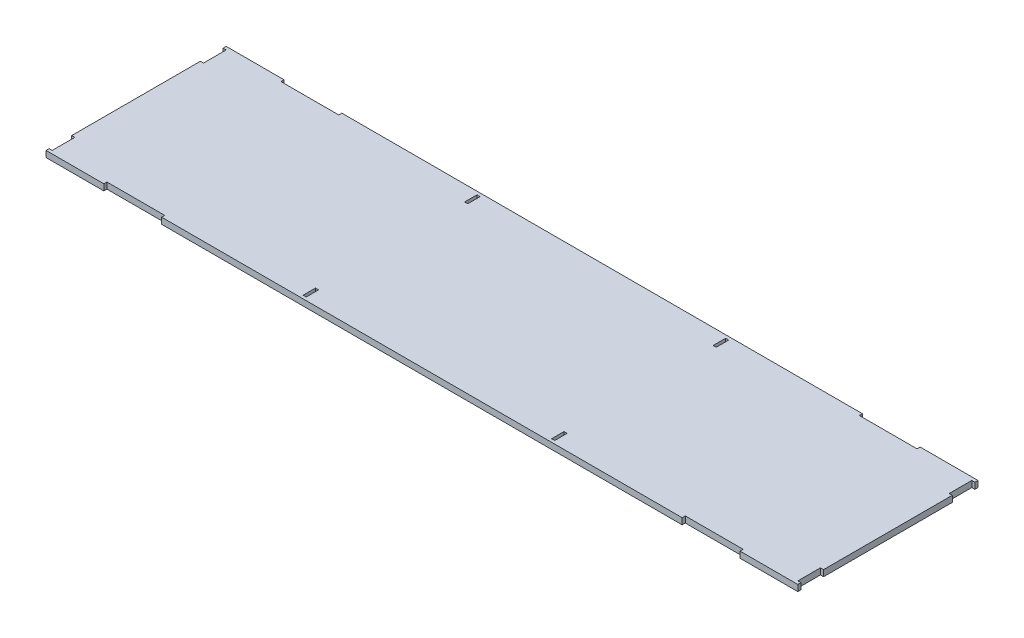
SolidWorks part; units mm, degrees
ref_plane "Front Plane" through (0, 0, 0) normal (0, 0, 1) x (1, 0, 0)
ref_plane "Top Plane" through (0, 0, 0) normal (0, 1, 0) x (1, 0, 0)
ref_plane "Right Plane" through (0, 0, 0) normal (1, 0, 0) x (0, 0, -1)
sketch "Sketch1" plane through (0, 0, 0) normal (0, 1, 0) x (1, 0, 0)
  line L0 (0, 88.9) -> (0, -88.9) construction
  line L1 (-381, 88.9) -> (381, 88.9)
  line L2 (-381, 88.9) -> (-381, -88.9)
  line L3 (-381, -88.9) -> (381, -88.9)
  line L4 (381, 88.9) -> (381, -88.9)
  line L5 (-381, 39.4607) -> (-381, 65.7679)
  line L6 (-381, 65.7679) -> (-384.175, 65.7679)
  line L7 (-381, 65.7679) -> (-381, 92.075)
  line L8 (-381, 92.075) -> (-384.175, 92.075)
  line L9 (-384.175, 65.7679) -> (-384.175, 92.075)
  line L14 (-325.0712, -88.9) -> (-384.175, -88.9)
  line L15 (-325.0712, -88.9) -> (-325.0712, -92.075)
  line L16 (-325.0712, -92.075) -> (-384.175, -92.075)
  line L17 (-384.175, -88.9) -> (-384.175, -92.075)
  line L18 (381, 65.7679) -> (384.175, 65.7679)
  line L19 (381, 65.7679) -> (381, 92.075)
  line L20 (381, 92.075) -> (384.175, 92.075)
  line L21 (384.175, 65.7679) -> (384.175, 92.075)
  line L22 (-325.0712, 88.9) -> (-384.175, 88.9)
  line L23 (-325.0712, 88.9) -> (-325.0712, 92.075)
  line L24 (-325.0712, 92.075) -> (-384.175, 92.075)
  line L25 (-384.175, 88.9) -> (-384.175, 92.075)
  line L26 (-381, 39.4607) -> (-384.175, 39.4607)
  line L27 (-384.175, 39.4607) -> (-384.175, 65.7679)
  line L28 (-381, 65.7679) -> (-384.175, 65.7679)
  line L29 (381, 39.4607) -> (381, 65.7679)
  line L30 (381, 39.4607) -> (384.175, 39.4607)
  line L31 (384.175, 39.4607) -> (384.175, 65.7679)
  line L32 (381, 65.7679) -> (384.175, 65.7679)
  line L33 (-381, 13.1536) -> (-381, 39.4607)
  line L34 (-381, 13.1536) -> (-384.175, 13.1536)
  line L35 (-384.175, 13.1536) -> (-384.175, 39.4607)
  line L36 (-381, 39.4607) -> (-384.175, 39.4607)
  line L37 (381, 13.1536) -> (381, 39.4607)
  line L38 (381, 13.1536) -> (384.175, 13.1536)
  line L39 (384.175, 13.1536) -> (384.175, 39.4607)
  line L40 (381, 39.4607) -> (384.175, 39.4607)
  line L41 (-381, -13.1536) -> (-381, 13.1536)
  line L42 (-381, -13.1536) -> (-384.175, -13.1536)
  line L43 (-384.175, -13.1536) -> (-384.175, 13.1536)
  line L44 (-381, 13.1536) -> (-384.175, 13.1536)
  line L45 (381, -13.1536) -> (381, 13.1536)
  line L46 (381, -13.1536) -> (384.175, -13.1536)
  line L47 (384.175, -13.1536) -> (384.175, 13.1536)
  line L48 (381, 13.1536) -> (384.175, 13.1536)
  line L49 (-381, -39.4607) -> (-381, -13.1536)
  line L50 (-381, -39.4607) -> (-384.175, -39.4607)
  line L51 (-384.175, -39.4607) -> (-384.175, -13.1536)
  line L52 (-381, -13.1536) -> (-384.175, -13.1536)
  line L53 (381, -39.4607) -> (381, -13.1536)
  line L54 (381, -39.4607) -> (384.175, -39.4607)
  line L55 (384.175, -39.4607) -> (384.175, -13.1536)
  line L56 (381, -13.1536) -> (384.175, -13.1536)
  line L57 (-381, -65.7679) -> (-381, -39.4607)
  line L58 (-381, -65.7679) -> (-384.175, -65.7679)
  line L59 (-384.175, -65.7679) -> (-384.175, -39.4607)
  line L60 (-381, -39.4607) -> (-384.175, -39.4607)
  line L61 (381, -65.7679) -> (381, -39.4607)
  line L62 (381, -65.7679) -> (384.175, -65.7679)
  line L63 (384.175, -65.7679) -> (384.175, -39.4607)
  line L64 (381, -39.4607) -> (384.175, -39.4607)
  line L65 (-381, -92.075) -> (-381, -65.7679)
  line L66 (-381, -92.075) -> (-384.175, -92.075)
  line L67 (-384.175, -92.075) -> (-384.175, -65.7679)
  line L68 (-381, -65.7679) -> (-384.175, -65.7679)
  line L69 (381, -92.075) -> (381, -65.7679)
  line L70 (381, -92.075) -> (384.175, -92.075)
  line L71 (384.175, -92.075) -> (384.175, -65.7679)
  line L72 (381, -65.7679) -> (384.175, -65.7679)
  line L73 (-265.9673, -88.9) -> (-265.9673, -92.075)
  line L74 (-265.9673, -88.9) -> (-325.0712, -88.9)
  line L75 (-325.0712, -88.9) -> (-325.0712, -92.075)
  line L76 (-265.9673, -92.075) -> (-325.0712, -92.075)
  line L77 (-265.9673, 88.9) -> (-265.9673, 92.075)
  line L78 (-265.9673, 88.9) -> (-325.0712, 88.9)
  line L79 (-325.0712, 88.9) -> (-325.0712, 92.075)
  line L80 (-265.9673, 92.075) -> (-325.0712, 92.075)
  line L81 (-206.8635, -88.9) -> (-206.8635, -92.075)
  line L82 (-206.8635, -88.9) -> (-265.9673, -88.9)
  line L83 (-265.9673, -88.9) -> (-265.9673, -92.075)
  line L84 (-206.8635, -92.075) -> (-265.9673, -92.075)
  line L85 (-206.8635, 88.9) -> (-206.8635, 92.075)
  line L86 (-206.8635, 88.9) -> (-265.9673, 88.9)
  line L87 (-265.9673, 88.9) -> (-265.9673, 92.075)
  line L88 (-206.8635, 92.075) -> (-265.9673, 92.075)
  line L89 (-147.7596, -88.9) -> (-147.7596, -92.075)
  line L90 (-147.7596, -88.9) -> (-206.8635, -88.9)
  line L91 (-206.8635, -88.9) -> (-206.8635, -92.075)
  line L92 (-147.7596, -92.075) -> (-206.8635, -92.075)
  line L93 (-147.7596, 88.9) -> (-147.7596, 92.075)
  line L94 (-147.7596, 88.9) -> (-206.8635, 88.9)
  line L95 (-206.8635, 88.9) -> (-206.8635, 92.075)
  line L96 (-147.7596, 92.075) -> (-206.8635, 92.075)
  line L97 (-88.6558, -88.9) -> (-88.6558, -92.075)
  line L98 (-88.6558, -88.9) -> (-147.7596, -88.9)
  line L99 (-147.7596, -88.9) -> (-147.7596, -92.075)
  line L100 (-88.6558, -92.075) -> (-147.7596, -92.075)
  line L101 (-88.6558, 88.9) -> (-88.6558, 92.075)
  line L102 (-88.6558, 88.9) -> (-147.7596, 88.9)
  line L103 (-147.7596, 88.9) -> (-147.7596, 92.075)
  line L104 (-88.6558, 92.075) -> (-147.7596, 92.075)
  line L105 (-29.5519, -88.9) -> (-29.5519, -92.075)
  line L106 (-29.5519, -88.9) -> (-88.6558, -88.9)
  line L107 (-88.6558, -88.9) -> (-88.6558, -92.075)
  line L108 (-29.5519, -92.075) -> (-88.6558, -92.075)
  line L109 (-29.5519, 88.9) -> (-29.5519, 92.075)
  line L110 (-29.5519, 88.9) -> (-88.6558, 88.9)
  line L111 (-88.6558, 88.9) -> (-88.6558, 92.075)
  line L112 (-29.5519, 92.075) -> (-88.6558, 92.075)
  line L113 (29.5519, -88.9) -> (29.5519, -92.075)
  line L114 (29.5519, -88.9) -> (-29.5519, -88.9)
  line L115 (-29.5519, -88.9) -> (-29.5519, -92.075)
  line L116 (29.5519, -92.075) -> (-29.5519, -92.075)
  line L117 (29.5519, 88.9) -> (29.5519, 92.075)
  line L118 (29.5519, 88.9) -> (-29.5519, 88.9)
  line L119 (-29.5519, 88.9) -> (-29.5519, 92.075)
  line L120 (29.5519, 92.075) -> (-29.5519, 92.075)
  line L121 (88.6558, -88.9) -> (88.6558, -92.075)
  line L122 (88.6558, -88.9) -> (29.5519, -88.9)
  line L123 (29.5519, -88.9) -> (29.5519, -92.075)
  line L124 (88.6558, -92.075) -> (29.5519, -92.075)
  line L125 (88.6558, 88.9) -> (88.6558, 92.075)
  line L126 (88.6558, 88.9) -> (29.5519, 88.9)
  line L127 (29.5519, 88.9) -> (29.5519, 92.075)
  line L128 (88.6558, 92.075) -> (29.5519, 92.075)
  line L129 (147.7596, -88.9) -> (147.7596, -92.075)
  line L130 (147.7596, -88.9) -> (88.6558, -88.9)
  line L131 (88.6558, -88.9) -> (88.6558, -92.075)
  line L132 (147.7596, -92.075) -> (88.6558, -92.075)
  line L133 (147.7596, 88.9) -> (147.7596, 92.075)
  line L134 (147.7596, 88.9) -> (88.6558, 88.9)
  line L135 (88.6558, 88.9) -> (88.6558, 92.075)
  line L136 (147.7596, 92.075) -> (88.6558, 92.075)
  line L137 (206.8635, -88.9) -> (206.8635, -92.075)
  line L138 (206.8635, -88.9) -> (147.7596, -88.9)
  line L139 (147.7596, -88.9) -> (147.7596, -92.075)
  line L140 (206.8635, -92.075) -> (147.7596, -92.075)
  line L141 (206.8635, 88.9) -> (206.8635, 92.075)
  line L142 (206.8635, 88.9) -> (147.7596, 88.9)
  line L143 (147.7596, 88.9) -> (147.7596, 92.075)
  line L144 (206.8635, 92.075) -> (147.7596, 92.075)
  line L145 (265.9673, -88.9) -> (265.9673, -92.075)
  line L146 (265.9673, -88.9) -> (206.8635, -88.9)
  line L147 (206.8635, -88.9) -> (206.8635, -92.075)
  line L148 (265.9673, -92.075) -> (206.8635, -92.075)
  line L149 (265.9673, 88.9) -> (265.9673, 92.075)
  line L150 (265.9673, 88.9) -> (206.8635, 88.9)
  line L151 (206.8635, 88.9) -> (206.8635, 92.075)
  line L152 (265.9673, 92.075) -> (206.8635, 92.075)
  line L185 (325.0712, -88.9) -> (325.0712, -92.075)
  line L186 (325.0712, -88.9) -> (265.9673, -88.9)
  line L187 (265.9673, -88.9) -> (265.9673, -92.075)
  line L188 (325.0712, -92.075) -> (265.9673, -92.075)
  line L189 (325.0712, 88.9) -> (325.0712, 92.075)
  line L190 (325.0712, 88.9) -> (265.9673, 88.9)
  line L191 (265.9673, 88.9) -> (265.9673, 92.075)
  line L192 (325.0712, 92.075) -> (265.9673, 92.075)
  line L193 (384.175, -88.9) -> (384.175, -92.075)
  line L194 (384.175, -88.9) -> (325.0712, -88.9)
  line L195 (325.0712, -88.9) -> (325.0712, -92.075)
  line L196 (384.175, -92.075) -> (325.0712, -92.075)
  line L197 (384.175, 88.9) -> (384.175, 92.075)
  line L198 (384.175, 88.9) -> (325.0712, 88.9)
  line L199 (325.0712, 88.9) -> (325.0712, 92.075)
  line L200 (384.175, 92.075) -> (325.0712, 92.075)
  point P8 (0, 88.9)
  point P9 (0, 0)
  dimension "D1" = 762
  dimension "D2" = 177.8
  dimension "D3" = 184.15
  dimension "D5" = 768.35
  dimension "D6" = 26.3071
  dimension "D8" = 59.1038
  dimension "D4" = 7
  dimension "D7" = 13
extrude "Boss-Extrude1" add sketch "Sketch1" along normal blind 6.35
sketch "Sketch2" plane through (0, 6.35, 0) normal (0, 1, 0) x (1, 0, 0)
  line L0 (-125.4125, 0) -> (125.4125, 0) construction
  line L1 (-128.5875, 15.4404) -> (-125.4125, 15.4404) construction
  line L2 (-128.5875, 15.4404) -> (-128.5875, -15.4404) construction
  line L3 (-128.5875, -15.4404) -> (-125.4125, -15.4404) construction
  line L4 (-125.4125, 15.4404) -> (-125.4125, -15.4404) construction
  line L5 (125.4125, 14.3164) -> (128.5875, 14.3164) construction
  line L6 (125.4125, 14.3164) -> (125.4125, -14.3164) construction
  line L7 (125.4125, -14.3164) -> (128.5875, -14.3164) construction
  line L8 (128.5875, 14.3164) -> (128.5875, -14.3164) construction
  line L9 (-129.3813, 24.6215) -> (-124.6188, 24.6215) construction
  line L10 (-127, 24.6215) -> (-127, 15.4404) construction
  line L12 (-124.6188, 76.2) -> (-121.4438, 76.2)
  line L13 (-124.6188, 76.2) -> (-124.6188, 88.9)
  line L14 (-124.6188, 88.9) -> (-121.4438, 88.9)
  line L15 (-121.4438, 76.2) -> (-121.4438, 88.9)
  line L16 (-124.6188, 24.6215) -> (-124.6188, 76.2) construction
  line L18 (-121.4438, -88.9) -> (-124.6188, -88.9)
  line L19 (-121.4438, -88.9) -> (-121.4438, -76.2)
  line L20 (-121.4438, -76.2) -> (-124.6188, -76.2)
  line L21 (-124.6188, -88.9) -> (-124.6188, -76.2)
  line L31 (-206.8635, 88.9) -> (-147.7596, 88.9) construction
  line L32 (-206.8635, -88.9) -> (-147.7596, -88.9) construction
  line L33 (129.3813, 76.2) -> (129.3812, 88.9)
  line L34 (129.3813, 76.2) -> (132.5562, 76.2)
  line L35 (132.5562, 76.2) -> (132.5562, 88.9)
  line L36 (129.3812, 88.9) -> (132.5562, 88.9)
  line L37 (132.5562, -88.9) -> (132.5562, -76.2)
  line L38 (132.5562, -88.9) -> (129.3812, -88.9)
  line L39 (129.3812, -88.9) -> (129.3812, -76.2)
  line L40 (132.5562, -76.2) -> (129.3812, -76.2)
  line L41 (124.6188, 24.6215) -> (129.3813, 24.6215) construction
  line L42 (127, 24.6215) -> (127, 14.3164) construction
  line L43 (129.3813, 24.6215) -> (129.3813, 76.2) construction
  point P10 (0, 0)
  point P43 (127, 14.3164)
  dimension "D1" = 3.175
  dimension "D2" = 4.7625
  dimension "D4" = 3.175
  dimension "D5" = 12.7
  dimension "D3" = 254
  dimension "D6" = 2
extrude "Cut-Extrude1" cut sketch "Sketch2" against normal through all
sketch "Sketch3" plane through (0, 6.35, 0) normal (0, 1, 0) x (1, 0, 0)
  line L1 (-206.8635, -92.075) -> (-147.7596, -92.075)
  line L2 (-206.8635, -92.075) -> (-206.8635, -88.9)
  line L3 (-206.8635, -88.9) -> (-147.7596, -88.9)
  line L4 (-147.7596, -92.075) -> (-147.7596, -88.9)
  line L5 (-88.6558, -92.075) -> (-29.5519, -92.075)
  line L6 (-88.6558, -92.075) -> (-88.6558, -88.9)
  line L7 (-88.6558, -88.9) -> (-29.5519, -88.9)
  line L8 (-29.5519, -92.075) -> (-29.5519, -88.9)
  line L9 (29.5519, -92.075) -> (88.6558, -92.075)
  line L10 (29.5519, -92.075) -> (29.5519, -88.9)
  line L11 (29.5519, -88.9) -> (88.6558, -88.9)
  line L12 (88.6558, -92.075) -> (88.6558, -88.9)
  line L13 (147.7596, -92.075) -> (206.8635, -92.075)
  line L14 (147.7596, -92.075) -> (147.7596, -88.9)
  line L15 (147.7596, -88.9) -> (206.8635, -88.9)
  line L16 (206.8635, -92.075) -> (206.8635, -88.9)
  line L17 (384.175, -39.4607) -> (381, -39.4607)
  line L18 (384.175, -39.4607) -> (384.175, -13.1536)
  line L19 (384.175, -13.1536) -> (381, -13.1536)
  line L20 (381, -39.4607) -> (381, -13.1536)
  line L21 (384.175, 13.1536) -> (381, 13.1536)
  line L22 (384.175, 13.1536) -> (384.175, 39.4607)
  line L23 (384.175, 39.4607) -> (381, 39.4607)
  line L24 (381, 13.1536) -> (381, 39.4607)
  line L25 (-384.175, -13.1536) -> (-381, -13.1536)
  line L26 (-384.175, -13.1536) -> (-384.175, -39.4607)
  line L27 (-384.175, -39.4607) -> (-381, -39.4607)
  line L28 (-381, -13.1536) -> (-381, -39.4607)
  line L29 (-384.175, 39.4607) -> (-381, 39.4607)
  line L30 (-384.175, 39.4607) -> (-384.175, 13.1536)
  line L31 (-384.175, 13.1536) -> (-381, 13.1536)
  line L32 (-381, 39.4607) -> (-381, 13.1536)
  line L33 (-206.8635, 88.9) -> (-147.7596, 88.9)
  line L34 (-206.8635, 88.9) -> (-206.8635, 92.075)
  line L35 (-206.8635, 92.075) -> (-147.7596, 92.075)
  line L36 (-147.7596, 88.9) -> (-147.7596, 92.075)
  line L37 (-88.6558, 88.9) -> (-29.5519, 88.9)
  line L38 (-88.6558, 88.9) -> (-88.6558, 92.075)
  line L39 (-88.6558, 92.075) -> (-29.5519, 92.075)
  line L40 (-29.5519, 88.9) -> (-29.5519, 92.075)
  line L41 (29.5519, 88.9) -> (88.6558, 88.9)
  line L42 (29.5519, 88.9) -> (29.5519, 92.075)
  line L43 (29.5519, 92.075) -> (88.6558, 92.075)
  line L44 (88.6558, 88.9) -> (88.6558, 92.075)
  line L45 (147.7596, 88.9) -> (206.8635, 88.9)
  line L46 (147.7596, 88.9) -> (147.7596, 92.075)
  line L47 (147.7596, 92.075) -> (206.8635, 92.075)
  line L48 (206.8635, 88.9) -> (206.8635, 92.075)
extrude "Boss-Extrude2" add sketch "Sketch3" against normal up to surface (6.35 mm away) up to face at (130.9687, 0, -82.55)
equation "\"Height\"= 12in"
equation "\"Depth\"= 7in"
equation "\"WallThickness\"= 0.125in"
equation "\"FloorThickness\"= 0.25in"
equation "\"D1@Sketch1\"=\"Width\""
equation "\"D2@Sketch1\"=\"Depth\""
equation "\"D3@Sketch1\"=\"D2@Sketch1\"+2*\"WallThickness\""
equation "\"D5@Sketch1\"=\"D1@Sketch1\"+2*\"WallThickness\""
equation "\"D6@Sketch1\"=\"D3@Sketch1\"/\"D4@Sketch1\""
equation "\"D8@Sketch1\"=\"D5@Sketch1\"/\"D7@Sketch1\""
equation "\"D1@Boss-Extrude1\"=\"FloorThickness\""
equation "\"D1@Sketch2\"=\"WallThickness\""
equation "\"D2@Sketch2\"=\"WallThickness\"+(1/16in)"
equation "\"D4@Sketch2\"=\"WallThickness\""
equation "\"Width\" = 30in"
